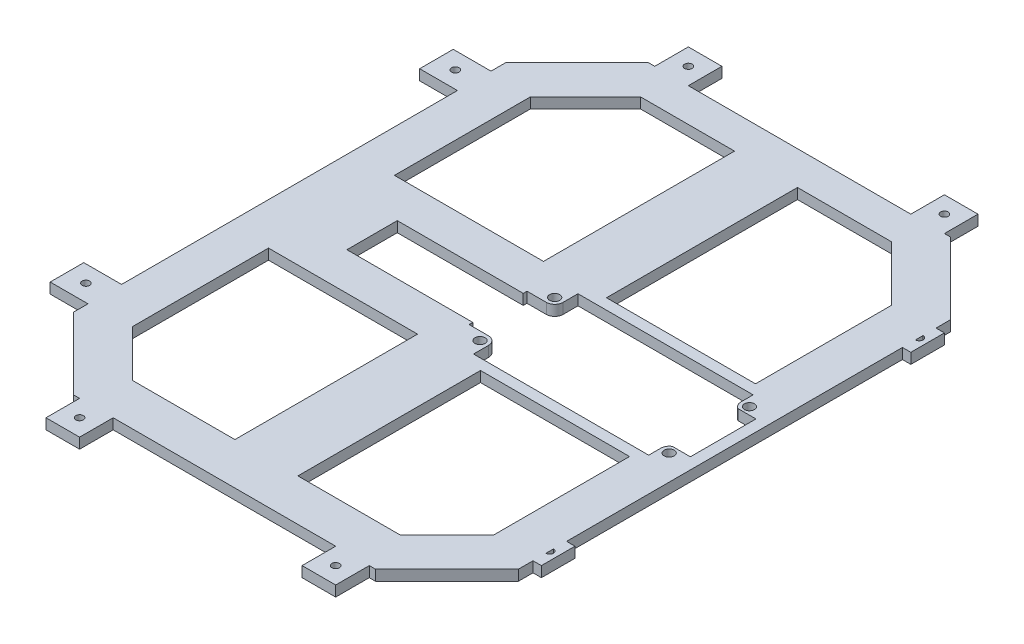
SolidWorks part; units mm, degrees
ref_plane "Front Plane" through (0, 0, 0) normal (0, 0, 1) x (1, 0, 0)
ref_plane "Top Plane" through (0, 0, 0) normal (0, 1, 0) x (1, 0, 0)
ref_plane "Right Plane" through (0, 0, 0) normal (1, 0, 0) x (0, 0, -1)
sketch "Sketch1" plane through (0, 0, 0) normal (0, 1, 0) x (1, 0, 0)
  line L1 (0, 0) -> (106, 0)
  line L2 (0, 0) -> (0, -137)
  line L3 (0, -137) -> (106, -137)
  line L4 (106, 0) -> (106, -137)
  line L5 (0, 0) -> (106, -137) construction
  line L6 (0, -137) -> (106, 0) construction
  point P4 (53, -68.5)
  dimension "D1" = 137
  dimension "D2" = 106
extrude "Boss-Extrude1" add sketch "Sketch1" along normal blind 2.5
sketch "Sketch2" plane through (0, 2.5, 0) normal (0, 1, 0) x (1, 0, 0)
  line L0 (0, -120) -> (17, -137)
  line L1 (0, 0) -> (0, -137) construction
  line L2 (0, -137) -> (106, -137) construction
  line L3 (17, -137) -> (0, -137)
  line L4 (0, -137) -> (0, -120)
  line L5 (89, -137) -> (106, -120)
  line L6 (106, -137) -> (106, 0) construction
  line L7 (106, -120) -> (106, -137)
  line L8 (106, -137) -> (89, -137)
  line L9 (89, 0) -> (106, -17)
  line L10 (106, 0) -> (0, 0) construction
  line L11 (106, -17) -> (106, 0)
  line L12 (106, 0) -> (89, 0)
  line L13 (0, 0) -> (17, 0)
  line L14 (17, 0) -> (0, -17)
  line L15 (0, -17) -> (0, 0)
  line L16 (10, -21.1421) -> (23.1421, -8)
  line L17 (23.1421, -8) -> (45.5, -8)
  line L18 (82.8579, -8) -> (96, -21.1421)
  line L19 (96, -21.1421) -> (96, -53.5)
  line L20 (96, -115.8579) -> (84.8579, -127)
  line L21 (84.8579, -127) -> (60.5, -127)
  line L22 (21.1421, -127) -> (10, -115.8579)
  line L23 (10, -115.8579) -> (10, -83.5)
  line L24 (96, -83.5) -> (96, -53.5) construction
  line L25 (10, -83.5) -> (45.5, -83.5)
  line L27 (10, -53.5) -> (45.5, -53.5)
  line L29 (0, -68.5) -> (106, -68.5) construction
  line L30 (45.5, -127) -> (21.1421, -127)
  line L31 (96, -83.5) -> (96, -115.8579)
  line L33 (10, -53.5) -> (10, -21.1421)
  line L34 (45.5, -127) -> (45.5, -83.5)
  line L36 (60.5, -127) -> (60.5, -83.5)
  line L37 (60.5, -53.5) -> (96, -53.5)
  line L38 (60.5, -8) -> (82.8579, -8)
  line L40 (45.5, -53.5) -> (45.5, -8)
  line L42 (60.5, -53.5) -> (60.5, -8)
  line L43 (60.5, -83.5) -> (96, -83.5)
  line L44 (53, -137) -> (53, 0) construction
  line L45 (45.5, -127) -> (60.5, -127) construction
  point P38 (96, -68.5)
  point P43 (53, -127)
  line M40 (0, 0) -> (0, -137)
  line M41 (0, -137) -> (106, -137)
  line M42 (106, -137) -> (106, 0)
  line M43 (106, 0) -> (0, 0)
  dimension "D1" = 17
  dimension "D2" = 17
  dimension "D3" = 17
  dimension "D4" = 17
  dimension "D5" = 17
  dimension "D6" = 17
  dimension "D7" = 17
  dimension "D8" = 17
  dimension "D9" = 8
  dimension "D10" = 10
  dimension "D11" = 10
  dimension "D12" = 10
  dimension "D13" = 10
  dimension "D14" = 10
  dimension "D15" = 10
  dimension "D16" = 10
  dimension "D17" = 30
  dimension "D18" = 15
  dimension "D19" = 15
extrude "Cut-Extrude1" cut sketch "Sketch2" against normal through all both and the other way through all contours L43 L36 L21 L20 L31 | L5 M41 M42 | L0 M40 M41 | L30 L34 L25 L23 L22 | L27 L40 L17 L16 L33 | L42 L37 L19 L18 L38 | L9 M43 M42 | L14 M43 M40
sketch "Sketch3" plane through (0, 2.5, 0) normal (0, 1, 0) x (1, 0, 0)
  line L0 (54.2756, -77.39) -> (54.2756, -59.61) construction
  line L5 (100, -78.0568) -> (100, -58.9433) construction
  line L7 (106, -120) -> (106, -17) construction
  line L8 (106, -68.5) -> (0, -68.5) construction
  line L9 (0, -17) -> (0, -120) construction
  line L10 (56.2756, -80.94) -> (98, -80.94)
  line L15 (98, -80.94) -> (98, -78.0568)
  line L16 (100, -76.0568) -> (103.3, -76.0568)
  line L21 (103.3, -76.0568) -> (103.3, -60.9433)
  line L22 (103.3, -60.9433) -> (100, -60.9433)
  line L27 (98, -58.9433) -> (98, -56.06)
  line L28 (98, -56.06) -> (56.2756, -56.06)
  line L29 (56.2756, -56.06) -> (56.2756, -59.61)
  line L30 (56.2756, -77.39) -> (56.2756, -80.94)
  line L31 (54.2756, -75.39) -> (49.6756, -75.39)
  line L32 (49.6756, -75.39) -> (49.6756, -61.61)
  line L34 (54.2756, -61.61) -> (49.6756, -61.61)
  line L36 (103.3, -76.0568) -> (99.0318, -76.0568)
  line L37 (103.3, -76.0568) -> (103.3, -76.3068)
  line L38 (103.3, -76.3068) -> (99.0318, -76.3068)
  line L39 (99.0318, -76.0568) -> (99.0318, -76.3068)
  line L40 (103.3, -76.0568) -> (99.0318, -76.3068) construction
  line L41 (103.3, -76.3068) -> (99.0318, -76.0568) construction
  line L42 (103.3, -60.9433) -> (97.0368, -60.9433)
  line L43 (103.3, -60.9433) -> (103.3, -60.6933)
  line L44 (103.3, -60.6933) -> (97.0368, -60.6933)
  line L45 (97.0368, -60.9433) -> (97.0368, -60.6933)
  line L46 (103.3, -60.9433) -> (97.0368, -60.6933) construction
  line L47 (103.3, -60.6933) -> (97.0368, -60.9433) construction
  circle A0 centre (54.2756, -77.39) radius 2
  circle A1 centre (54.2756, -59.61) radius 2
  circle A2 centre (100, -78.0568) radius 2
  circle A3 centre (100, -58.9433) radius 2
  circle A4 centre (54.2756, -77.39) radius 1.2
  circle A5 centre (54.2756, -59.61) radius 1.2
  circle A6 centre (100, -58.9433) radius 1.2
  circle A7 centre (100, -78.0568) radius 1.2
  arc A8 (54.2756, -75.39) -> (56.2756, -77.39) centre (54.2756, -77.39) cw
  arc A9 (56.2756, -59.61) -> (52.2756, -59.61) centre (54.2756, -59.61) cw
  arc A10 (98, -58.9433) -> (100, -60.9433) centre (100, -58.9433) ccw
  arc A11 (98, -78.0568) -> (100, -76.0568) centre (100, -78.0568) cw
  point P10 (54.2756, -68.5)
  point P11 (100, -68.5)
  point P24 (77.2368, -68.8611)
  point P34 (100.0995, -68.5)
  point P47 (101.1659, -76.1818)
  point P50 (100.1684, -60.8183)
  point P51 (0, 0)
  point P52 (0, 0)
  dimension "D4" = 4
  dimension "D5" = 4
  dimension "D6" = 4
  dimension "D7" = 4
  dimension "D8" = 2.4
  dimension "D9" = 2.4
  dimension "D10" = 2.4
  dimension "D11" = 2.4
  dimension "D12" = 6
  dimension "D1" = 19.1135
  dimension "D2" = 17.78
  dimension "D3" = 45.7244
  dimension "D13" = 4.6
  dimension "D14" = 3.3
  dimension "D15" = 3.55
  dimension "D16" = 3.55
  dimension "D17" = 0.25
  dimension "D18" = 0.25
sketch "Sketch5" plane through (0, 0, 0) normal (0, 1, 0) x (1, 0, 0)
  line L0 (0, -68.5) -> (106, -68.5) construction
  line L1 (-4.5, -112.5) -> (110.5, -112.5) construction
  line L2 (-4.5, -112.5) -> (-4.5, -24.5) construction
  line L3 (-4.5, -24.5) -> (110.5, -24.5) construction
  line L4 (110.5, -112.5) -> (110.5, -24.5) construction
  line L5 (-4.5, -112.5) -> (110.5, -24.5) construction
  line L6 (-4.5, -24.5) -> (110.5, -112.5) construction
  line L7 (22.5, 4) -> (83.5, 4) construction
  line L8 (22.5, 4) -> (22.5, -141) construction
  line L9 (22.5, -141) -> (83.5, -141) construction
  line L10 (83.5, 4) -> (83.5, -141) construction
  line L11 (22.5, 4) -> (83.5, -141) construction
  line L12 (22.5, -141) -> (83.5, 4) construction
  line L13 (0, -17) -> (0, -120) construction
  line L14 (106, -120) -> (106, -17) construction
  line L15 (53, -137) -> (53, 0) construction
  line L16 (17, -137) -> (89, -137) construction
  line L17 (89, 0) -> (17, 0) construction
  line L19 (18.5, -137) -> (26.5, -137)
  line L20 (18.5, -137) -> (18.5, -145)
  line L21 (18.5, -145) -> (26.5, -145)
  line L22 (26.5, -137) -> (26.5, -145)
  line L23 (18.5, -137) -> (26.5, -145) construction
  line L24 (18.5, -145) -> (26.5, -137) construction
  line L25 (87.5, -137) -> (79.5, -137)
  line L26 (87.5, -137) -> (87.5, -145)
  line L27 (87.5, -145) -> (79.5, -145)
  line L28 (79.5, -137) -> (79.5, -145)
  line L29 (87.5, -137) -> (79.5, -145) construction
  line L30 (87.5, -145) -> (79.5, -137) construction
  line L31 (87.5, 0) -> (79.5, 0)
  line L32 (87.5, 0) -> (87.5, 8)
  line L33 (87.5, 8) -> (79.5, 8)
  line L34 (79.5, 0) -> (79.5, 8)
  line L35 (87.5, 0) -> (79.5, 8) construction
  line L36 (87.5, 8) -> (79.5, 0) construction
  line L37 (18.5, 0) -> (26.5, 0)
  line L38 (18.5, 0) -> (18.5, 8)
  line L39 (18.5, 8) -> (26.5, 8)
  line L40 (26.5, 0) -> (26.5, 8)
  line L41 (18.5, 0) -> (26.5, 8) construction
  line L42 (18.5, 8) -> (26.5, 0) construction
  line L43 (0, -116.5) -> (-9, -116.5)
  line L44 (0, -116.5) -> (0, -108.5)
  line L45 (0, -108.5) -> (-9, -108.5)
  line L46 (-9, -116.5) -> (-9, -108.5)
  line L47 (0, -116.5) -> (-9, -108.5) construction
  line L48 (0, -108.5) -> (-9, -116.5) construction
  line L49 (0, -28.5) -> (-9, -28.5)
  line L50 (0, -28.5) -> (0, -20.5)
  line L51 (0, -20.5) -> (-9, -20.5)
  line L52 (-9, -28.5) -> (-9, -20.5)
  line L53 (0, -28.5) -> (-9, -20.5) construction
  line L54 (0, -20.5) -> (-9, -28.5) construction
  line L59 (106, -116.5) -> (108, -116.5)
  line L60 (106, -116.5) -> (106, -108.5)
  line L65 (106, -108.5) -> (108, -108.5)
  line L66 (108, -116.5) -> (108, -108.5)
  line L67 (106, -116.5) -> (108, -108.5) construction
  line L68 (106, -108.5) -> (108, -116.5) construction
  line L69 (106, -28.5) -> (108, -28.5)
  line L70 (106, -28.5) -> (106, -20.5)
  line L71 (106, -20.5) -> (108, -20.5)
  line L72 (108, -28.5) -> (108, -20.5)
  line L73 (106, -28.5) -> (108, -20.5) construction
  line L74 (106, -20.5) -> (108, -28.5) construction
  circle A0 centre (-4.5, -112.5) radius 0.9
  circle A1 centre (-4.5, -24.5) radius 0.9
  circle A2 centre (22.5, 4) radius 0.9
  circle A3 centre (83.5, 4) radius 0.9
  circle A6 centre (83.5, -141) radius 0.9
  circle A7 centre (22.5, -141) radius 0.9
  circle A8 centre (106, -112.5) radius 0.9
  circle A9 centre (106, -24.5) radius 0.9
  point P4 (53, -68.5)
  point P9 (53, -68.5)
  point P28 (22.5, -141)
  point P32 (83.5, -141)
  point P37 (83.5, 4)
  point P42 (22.5, 4)
  point P48 (-4.5, -112.5)
  point P52 (-4.5, -24.5)
  point P57 (107, -112.5)
  point P62 (107, -24.5)
  dimension "D13" = 1.8
  dimension "D14" = 1.8
  dimension "D15" = 1.8
  dimension "D16" = 1.8
  dimension "D17" = 8
  dimension "D18" = 2
  dimension "D19" = 1.8
  dimension "D20" = 1.8
  dimension "D21" = 1.8
  dimension "D22" = 1.8
  dimension "D1" = 61
  dimension "D2" = 145
  dimension "D3" = 88
  dimension "D4" = 115
  dimension "D5" = 8
  dimension "D6" = 8
  dimension "D7" = 8
  dimension "D8" = 8
  dimension "D9" = 8
  dimension "D10" = 8
  dimension "D11" = 2
  dimension "D12" = 8
extrude "Boss-Extrude4" add sketch "Sketch5" along normal up to surface (2.5 mm away) contours A8 L60 L59 L66 L65 | L25 L28 L27 L26 A6 | L22 L19 L20 L21 A7 | L46 L43 L44 L45 A0 | L52 L49 L50 L51 A1 | L37 L40 L39 L38 A2 | L34 L31 L32 L33 A3 | A9 L70 L69 L72 L71
ref_plane "Plane1" through (53, 0, 0) normal (-1, 0, 0) x (0, 0, 1)
ref_plane "Plane2" through (0, 0, 68.5) normal (0, 0, 1) x (1, 0, 0)
extrude "Cut-Extrude4" cut sketch "Sketch3" against normal through all both and the other way through all
sketch "Sketch7" plane through (0, 2.5, 0) normal (0, 1, 0) x (1, 0, 0)
  line L0 (49.6756, -75.39) -> (49.6756, -61.61) construction
  line L1 (49.6756, -62.5) -> (19.6756, -62.5)
  line L2 (49.6756, -62.5) -> (49.6756, -74.5)
  line L3 (49.6756, -74.5) -> (19.6756, -74.5)
  line L4 (19.6756, -62.5) -> (19.6756, -74.5)
  line L5 (49.6756, -62.5) -> (19.6756, -74.5) construction
  line L6 (49.6756, -74.5) -> (19.6756, -62.5) construction
  line L7 (49.6756, -68.5) -> (103.3, -68.5) construction
  line L8 (103.3, -76.3068) -> (103.3, -60.6933) construction
  point P4 (34.6756, -68.5)
  point P7 (49.6756, -68.5)
  dimension "D1" = 12
  dimension "D2" = 30
extrude "Cut-Extrude5" cut sketch "Sketch7" against normal through all both and the other way through all
